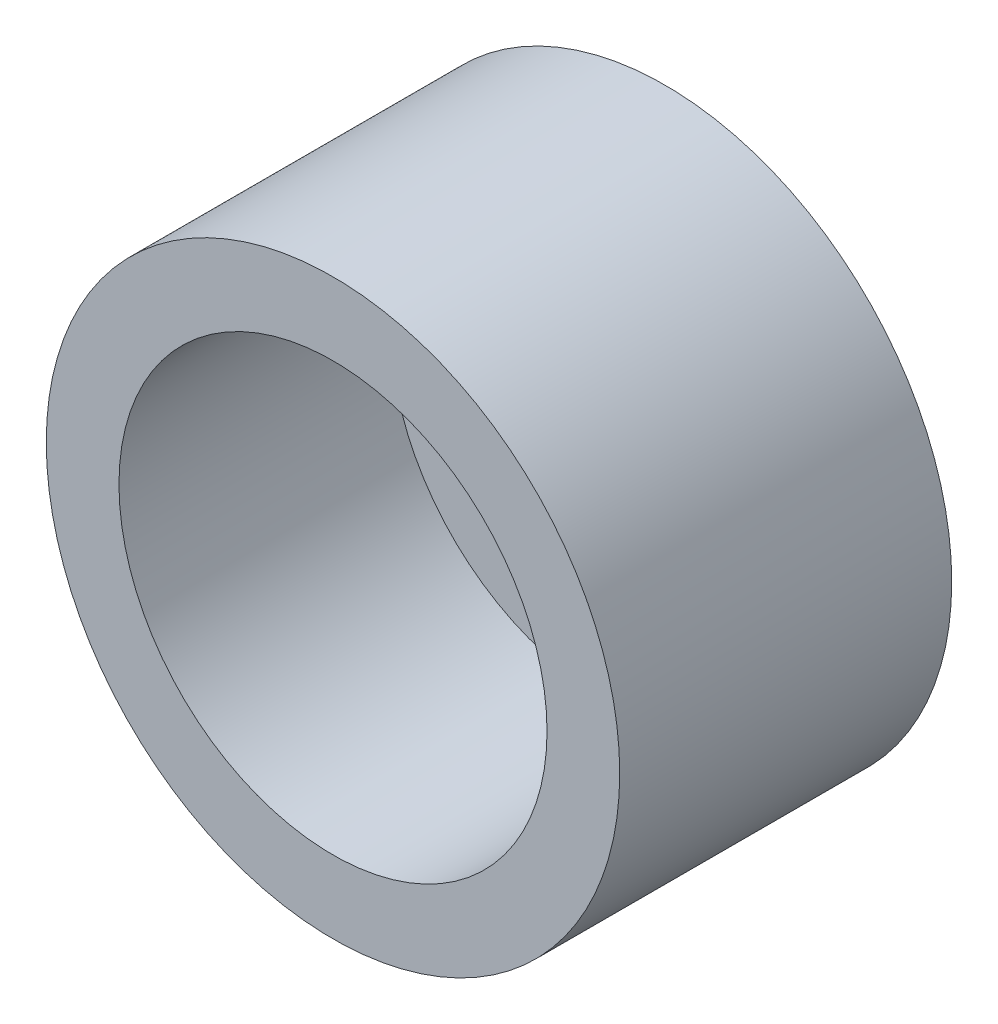
SolidWorks part; units mm, degrees
ref_plane "face" through (0, 0, 0) normal (0, 0, 1) x (1, 0, 0)
ref_plane "dessus" through (0, 0, 0) normal (0, 1, 0) x (1, 0, 0)
ref_plane "profil" through (0, 0, 0) normal (1, 0, 0) x (0, 0, -1)
sketch "section-extérieure" plane through (0, 0, 0) normal (0, 0, 1) x (1, 0, 0)
  circle A0 centre (0, 0) radius 9.5
  dimension "D1" = 19
extrude "extérieur" add sketch "section-extérieure" against normal blind 11
sketch "axe-douille" plane through (0, 0, 0) normal (0, 1, 0) x (1, 0, 0)
  line L0 (0, 0) -> (0, 20) construction
sketch "section interieure" plane through (0, 0, 0) normal (0, 0, 1) x (1, 0, 0)
  circle A0 centre (0, 0) radius 7.0915
  circle A1 centre (2.0798, -5.7255) radius 1 construction
extrude "intérieur" cut sketch "section interieure" against normal blind 9
